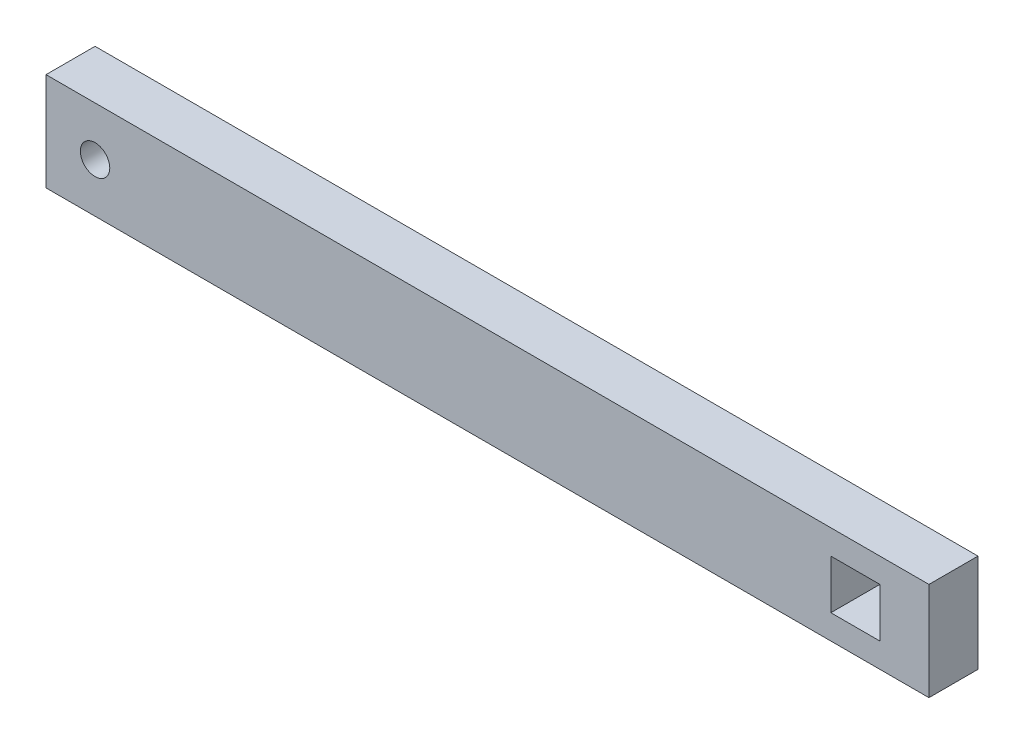
SolidWorks part; units mm, degrees
ref_plane "Plan de face" through (0, 0, 0) normal (0, 0, 1) x (1, 0, 0)
ref_plane "Plan de dessus" through (0, 0, 0) normal (0, 1, 0) x (1, 0, 0)
ref_plane "Plan de droite" through (0, 0, 0) normal (1, 0, 0) x (0, 0, -1)
sketch "Esquisse1" plane through (0, 0, 0) normal (0, 0, 1) x (1, 0, 0)
  line L0 (90, 5) -> (66.7705, 5) construction
  line L1 (0, 0) -> (90, 0)
  line L2 (0, 0) -> (0, 10)
  line L3 (0, 10) -> (90, 10)
  line L4 (90, 0) -> (90, 10)
  line L5 (85, 7.5) -> (80, 7.5)
  line L6 (85, 7.5) -> (85, 2.5)
  line L7 (85, 2.5) -> (80, 2.5)
  line L8 (80, 7.5) -> (80, 2.5)
  circle A0 centre (5, 5) radius 1.5
  dimension "D3" = 3
  dimension "D5" = 5
  dimension "D1" = 90
  dimension "D2" = 10
  dimension "D4" = 5
  dimension "D6" = 5
  dimension "D7" = 5
  dimension "D8" = 5
extrude "Boss.-Extru.1" add sketch "Esquisse1" along normal blind 5
